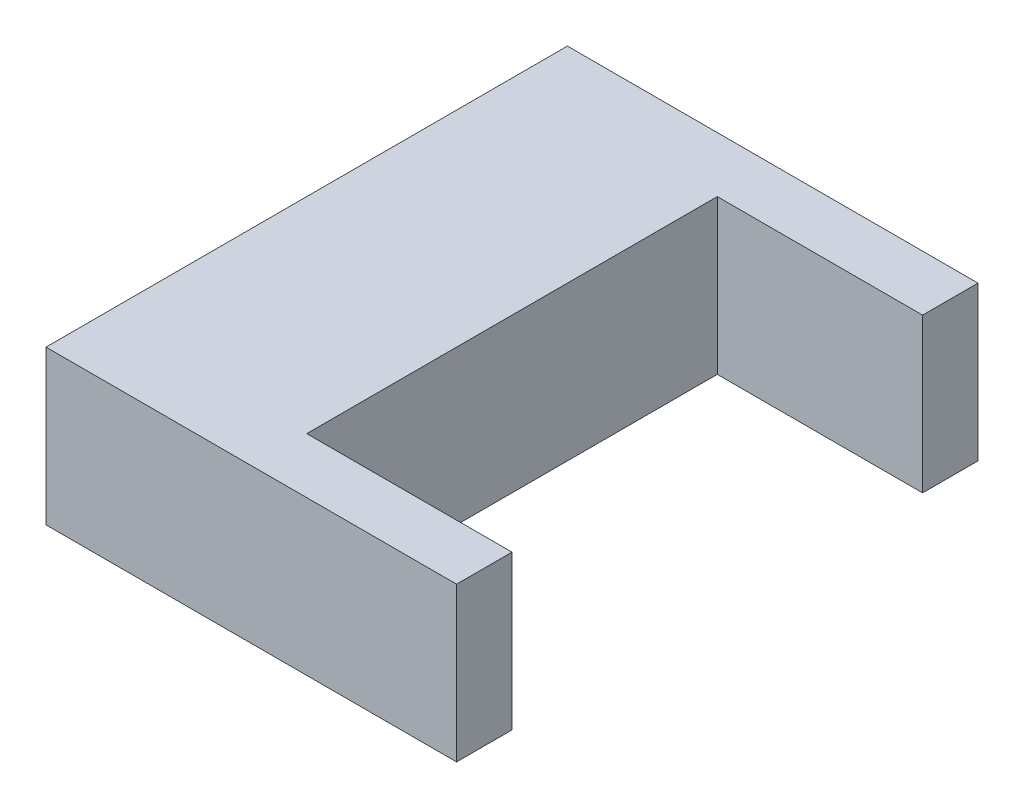
SolidWorks part; units mm, degrees
ref_plane "Front Plane" through (0, 0, 0) normal (0, 0, 1) x (1, 0, 0)
ref_plane "Top Plane" through (0, 0, 0) normal (0, 1, 0) x (1, 0, 0)
ref_plane "Right Plane" through (0, 0, 0) normal (1, 0, 0) x (0, 0, -1)
sketch "Sketch1" plane through (0, 0, 0) normal (0, 1, 0) x (1, 0, 0)
  line L0 (40, 20) -> (40, 25.4)
  line L1 (0, -25.4) -> (5, -25.4)
  line L2 (0, -25.4) -> (0, 25.4)
  line L3 (0, 25.4) -> (5, 25.4)
  line L7 (40, -20) -> (20, -20)
  line L9 (40, 20) -> (20, 20)
  line L10 (20, -20) -> (20, 20)
  line L13 (40, 25.4) -> (5, 25.4)
  line L14 (40, -20) -> (40, -25.4)
  line L15 (40, -25.4) -> (5, -25.4)
  point P0 (0, 0)
  point P12 (0, 0)
  point P14 (0, 0)
  dimension "D1" = 50.8
  dimension "D2" = 40
  dimension "D3" = 40
  dimension "D5" = 20
extrude "Boss-Extrude1" add sketch "Sketch1" along normal blind 15
